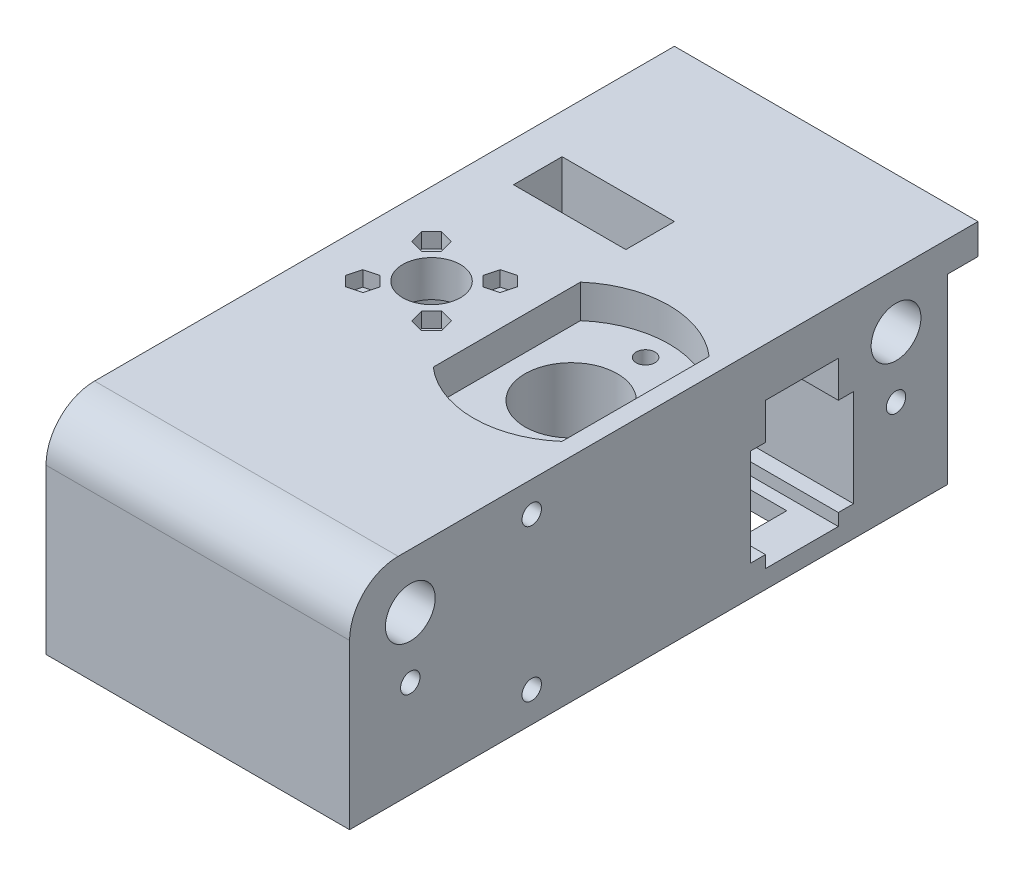
SolidWorks part; units mm, degrees
ref_plane "Front Plane" through (0, 0, 0) normal (0, 0, 1) x (1, 0, 0)
ref_plane "Top Plane" through (0, 0, 0) normal (0, 1, 0) x (1, 0, 0)
ref_plane "Right Plane" through (0, 0, 0) normal (1, 0, 0) x (0, 0, -1)
sketch "Sketch1" plane through (0, 0, 0) normal (1, 0, 0) x (0, 0, -1)
  line L0 (0, 0) -> (0, 30)
  line L1 (0, 30) -> (5, 30)
  line L2 (5, 30) -> (5, 35)
  line L3 (5, 35) -> (-98.5, 35)
  line L4 (-98.5, 35) -> (-98.5, 0)
  line L5 (-98.5, 0) -> (0, 0)
  dimension "D1" = 35
  dimension "D2" = 30
  dimension "D3" = 98.5
  dimension "D4" = 103.5
extrude "Boss-Extrude1" add sketch "Sketch1" along normal blind 50
sketch "Sketch2" plane through (0, 35, 0) normal (0, 1, 0) x (1, 0, 0)
  line L0 (50, 5) -> (50, -98.5) construction
  line L1 (50, 5) -> (0, 5) construction
  line L2 (36.5, -48.5) -> (13.5, -48.5) construction
  line L3 (36.5, -48.5) -> (36.5, -36.25) construction
  line L4 (36.5, -36.25) -> (36.5, -60.75) construction
  line L5 (13.5, -48.5) -> (13.5, -40.5) construction
  line L6 (13.5, -48.5) -> (19.1569, -42.8431) construction
  line L7 (13.5, -48.5) -> (7.8431, -42.8431) construction
  circle A0 centre (36.5, -48.5) radius 7.6
  circle A1 centre (13.5, -48.5) radius 4.75
  circle A2 centre (36.5, -36.25) radius 1.55
  circle A3 centre (36.5, -60.75) radius 1.55
  circle A4 centre (19.1569, -42.8431) radius 1.05
  circle A5 centre (19.1569, -54.1569) radius 1.05
  circle A6 centre (7.8431, -54.1569) radius 1.05
  circle A7 centre (7.8431, -42.8431) radius 1.05
  point P23 (13.5, -48.5)
  dimension "D1" = 15.2
  dimension "D2" = 13.5
  dimension "D3" = 53.5
  dimension "D5" = 9.5
  dimension "D8" = 3.1
  dimension "D9" = 3.1
  dimension "D13" = 2.1
  dimension "D16" = 11.3137
  dimension "D4" = 23
  dimension "D6" = 12.25
  dimension "D7" = 24.5
  dimension "D10" = 8
  dimension "D11" = 8
  dimension "D12" = 45
  dimension "D14" = 90
  dimension "D15" = 4
extrude "Cut-Extrude1" cut sketch "Sketch2" against normal through all
sketch "Sketch3" plane through (0, 35, 0) normal (0, 1, 0) x (1, 0, 0)
  line L0 (36.5, -32.4) -> (36.5, -64.6) construction
  line L1 (25.9, -36.3818) -> (25.9, -60.6182)
  line L2 (47.1, -36.3818) -> (47.1, -60.6182)
  arc A0 (25.9, -60.6182) -> (47.1, -60.6182) centre (36.5, -48.5) ccw
  arc A1 (47.1, -36.3818) -> (25.9, -36.3818) centre (36.5, -48.5) ccw
  dimension "D1" = 32.2
  dimension "D2" = 10.6
  dimension "D3" = 21.2
extrude "Cut-Extrude2" cut sketch "Sketch3" against normal blind 5.5
sketch "Sketch4" plane through (0, 0, 0) normal (0, -1, 0) x (1, 0, 0)
  circle A0 centre (13.5, 48.5) radius 11
  dimension "D1" = 22
extrude "Cut-Extrude3" cut sketch "Sketch4" against normal blind 29
sketch "Sketch5" plane through (0, 0, 0) normal (0, -1, 0) x (1, 0, 0)
  line L0 (36.5, 60.75) -> (41.5, 60.75) construction
  line L1 (36.5, 60.75) -> (38.1125, 63.5429) construction
  line L2 (36.5, 36.25) -> (41.5, 36.25) construction
  line L3 (39.725, 60.75) -> (38.1125, 63.5429)
  line L4 (38.1125, 63.5429) -> (34.8875, 63.5429)
  line L5 (34.8875, 63.5429) -> (33.275, 60.75)
  line L6 (33.275, 60.75) -> (34.8875, 57.9571)
  line L7 (34.8875, 57.9571) -> (38.1125, 57.9571)
  line L8 (38.1125, 57.9571) -> (39.725, 60.75)
  line L9 (38.1125, 39.0429) -> (34.8875, 39.0429)
  line L10 (34.8875, 39.0429) -> (33.275, 36.25)
  line L11 (33.275, 36.25) -> (34.8875, 33.4571)
  line L12 (34.8875, 33.4571) -> (38.1125, 33.4571)
  line L13 (38.1125, 33.4571) -> (39.725, 36.25)
  line L14 (39.725, 36.25) -> (38.1125, 39.0429)
  line L15 (38.1125, 39.0429) -> (36.5, 36.25) construction
  circle A0 centre (36.5, 60.75) radius 3.225 construction
  circle A1 centre (36.5, 36.25) radius 3.225 construction
  dimension "D3" = 6.45
  dimension "D4" = 6.45
  dimension "D1" = 5
  dimension "D2" = 5
  dimension "D5" = 60
  dimension "D6" = 60
extrude "Cut-Extrude4" cut sketch "Sketch5" against normal blind 5
sketch "Sketch6" plane through (0, 35, 0) normal (0, 1, 0) x (1, 0, 0)
  line L0 (19.1569, -42.8431) -> (24.1569, -42.8431) construction
  line L1 (19.1569, -42.8431) -> (21.3881, -42.2453) construction
  line L2 (21.3881, -42.2453) -> (19.7547, -40.6119)
  line L3 (19.7547, -40.6119) -> (17.5234, -41.2097)
  line L4 (17.5234, -41.2097) -> (16.9256, -43.441)
  line L5 (16.9256, -43.441) -> (18.559, -45.0744)
  line L6 (18.559, -45.0744) -> (20.7903, -44.4766)
  line L7 (20.7903, -44.4766) -> (21.3881, -42.2453)
  line L8 (19.1569, -42.8431) -> (13.5, -48.5) construction
  line L9 (21.3881, -54.7547) -> (20.7903, -52.5234)
  line L10 (20.7903, -52.5234) -> (18.559, -51.9256)
  line L11 (18.559, -51.9256) -> (16.9256, -53.559)
  line L12 (16.9256, -53.559) -> (17.5234, -55.7903)
  line L13 (17.5234, -55.7903) -> (19.7547, -56.3881)
  line L14 (19.7547, -56.3881) -> (21.3881, -54.7547)
  line L15 (7.2453, -56.3881) -> (9.4766, -55.7903)
  line L16 (9.4766, -55.7903) -> (10.0744, -53.559)
  line L17 (10.0744, -53.559) -> (8.441, -51.9256)
  line L18 (8.441, -51.9256) -> (6.2097, -52.5234)
  line L19 (6.2097, -52.5234) -> (5.6119, -54.7547)
  line L20 (5.6119, -54.7547) -> (7.2453, -56.3881)
  line L21 (5.6119, -42.2453) -> (6.2097, -44.4766)
  line L22 (6.2097, -44.4766) -> (8.441, -45.0744)
  line L23 (8.441, -45.0744) -> (10.0744, -43.441)
  line L24 (10.0744, -43.441) -> (9.4766, -41.2097)
  line L25 (9.4766, -41.2097) -> (7.2453, -40.6119)
  line L26 (7.2453, -40.6119) -> (5.6119, -42.2453)
  line L27 (7.8431, -42.8431) -> (13.5, -48.5) construction
  line L28 (7.8431, -42.8431) -> (9.4766, -41.2097) construction
  line L29 (7.8431, -42.8431) -> (10.0744, -43.441) construction
  circle A0 centre (19.1569, -42.8431) radius 2.31 construction
  circle A1 centre (19.1569, -54.1569) radius 2.31 construction
  circle A2 centre (7.8431, -54.1569) radius 2.31 construction
  circle A3 centre (7.8431, -42.8431) radius 2.31 construction
  point P38 (13.5, -48.5)
  dimension "D2" = 4.62
  dimension "D1" = 5
  dimension "D3" = 15
  dimension "D4" = 4
extrude "Cut-Extrude5" cut sketch "Sketch6" against normal blind 2.5
sketch "Sketch7" plane through (50, 0, 0) normal (1, 0, 0) x (0, 0, -1)
  line L0 (0, 0) -> (0, 30) construction
  line L1 (-30, 27) -> (-18, 27)
  line L2 (-30, 27) -> (-30, 3)
  line L3 (-30, 3) -> (-18, 3)
  line L4 (-18, 27) -> (-18, 3)
  line L5 (-98.5, 0) -> (0, 0) construction
  line L6 (5, 35) -> (-98.5, 35) construction
  line L7 (-8.5, 26) -> (-88.5, 26) construction
  line L8 (-88.5, 26) -> (-88.5, 16) construction
  line L9 (-8.5, 26) -> (-8.5, 16) construction
  line L10 (-88.5, 16) -> (-68.5, 30) construction
  line L11 (-68.5, 30) -> (-68.5, 5) construction
  circle A0 centre (-8.5, 26) radius 4.1
  circle A1 centre (-88.5, 26) radius 4.1
  circle A2 centre (-88.5, 16) radius 1.6
  circle A3 centre (-8.5, 16) radius 1.6
  circle A4 centre (-68.5, 30) radius 1.6
  circle A5 centre (-68.5, 5) radius 1.6
  dimension "D5" = 9
  dimension "D6" = 8.5
  dimension "D7" = 8.2
  dimension "D9" = 8.2
  dimension "D11" = 3.2
  dimension "D13" = 3.2
  dimension "D17" = 3.2
  dimension "D18" = 3.2
  dimension "D1" = 12
  dimension "D2" = 24
  dimension "D3" = 18
  dimension "D4" = 3
  dimension "D8" = 80
  dimension "D10" = 10
  dimension "D12" = 10
  dimension "D14" = 14
  dimension "D15" = 20
  dimension "D16" = 25
extrude "Cut-Extrude6" cut sketch "Sketch7" against normal through all
sketch "Sketch8" plane through (0, 0, 0) normal (-1, 0, 0) x (0, 0, 1)
  line L0 (8.5, 16) -> (13.8743, 16) construction
  line L1 (8.5, 16) -> (10.1125, 18.7929) construction
  line L2 (11.725, 16) -> (10.1125, 18.7929)
  line L3 (10.1125, 18.7929) -> (6.8875, 18.7929)
  line L4 (6.8875, 18.7929) -> (5.275, 16)
  line L5 (5.275, 16) -> (6.8875, 13.2071)
  line L6 (6.8875, 13.2071) -> (10.1125, 13.2071)
  line L7 (10.1125, 13.2071) -> (11.725, 16)
  line L8 (65.275, 30) -> (66.8875, 27.2071)
  line L9 (71.725, 30) -> (70.1125, 32.7929)
  line L10 (68.5, 30) -> (73.8743, 30) construction
  line L11 (70.1125, 27.2071) -> (71.725, 30)
  line L12 (70.1125, 32.7929) -> (66.8875, 32.7929)
  line L13 (68.5, 30) -> (70.1125, 32.7929) construction
  line L14 (66.8875, 27.2071) -> (70.1125, 27.2071)
  line L15 (66.8875, 32.7929) -> (65.275, 30)
  line L16 (65.275, 5) -> (66.8875, 2.2071)
  line L17 (71.725, 5) -> (70.1125, 7.7929)
  line L18 (68.5, 5) -> (73.8743, 5) construction
  line L19 (70.1125, 2.2071) -> (71.725, 5)
  line L20 (70.1125, 7.7929) -> (66.8875, 7.7929)
  line L21 (68.5, 5) -> (70.1125, 7.7929) construction
  line L22 (66.8875, 2.2071) -> (70.1125, 2.2071)
  line L23 (66.8875, 7.7929) -> (65.275, 5)
  line L24 (85.275, 16) -> (86.8875, 13.2071)
  line L25 (91.725, 16) -> (90.1125, 18.7929)
  line L26 (88.5, 16) -> (93.8743, 16) construction
  line L27 (90.1125, 13.2071) -> (91.725, 16)
  line L28 (90.1125, 18.7929) -> (86.8875, 18.7929)
  line L29 (88.5, 16) -> (90.1125, 18.7929) construction
  line L30 (86.8875, 13.2071) -> (90.1125, 13.2071)
  line L31 (86.8875, 18.7929) -> (85.275, 16)
  circle A0 centre (8.5, 16) radius 3.225 construction
  circle A1 centre (68.5, 30) radius 3.225 construction
  circle A2 centre (68.5, 5) radius 3.225 construction
  circle A3 centre (88.5, 16) radius 3.225 construction
  dimension "D1" = 6.45
  dimension "D2" = 60
  dimension "D3" = 80
  dimension "D4" = 14
  dimension "D5" = 25
  dimension "D6" = 60
  dimension "D7" = 60
extrude "Cut-Extrude7" cut sketch "Sketch8" against normal blind 35
sketch "Sketch9" plane through (50, 0, 0) normal (1, 0, 0) x (0, 0, -1)
  line L0 (-8.5, 26) -> (-8.5, 13) construction
  line L1 (-8.5, 13) -> (-24, 13) construction
  line L3 (-32.5, 5) -> (-15.5, 5)
  line L5 (-32.5, 21) -> (-15.5, 21)
  line L6 (-15.5, 5) -> (-15.5, 21)
  line L7 (-32.5, 5) -> (-15.5, 21) construction
  line L8 (-32.5, 21) -> (-15.5, 5) construction
  line L14 (-32.5, 5) -> (-32.5, 21)
  dimension "D1" = 13
  dimension "D2" = 15.5
  dimension "D3" = 17
  dimension "D4" = 16
extrude "Cut-Extrude8" cut sketch "Sketch9" against normal blind 48
sketch "Sketch10" plane through (0, 0, 0) normal (0, -1, 0) x (1, 0, 0)
  line L0 (43.5, 24) -> (6.5, 24) construction
  line L1 (6.5, 28) -> (43.5, 28)
  line L2 (6.5, 28) -> (6.5, 20)
  line L3 (6.5, 20) -> (43.5, 20)
  line L4 (43.5, 28) -> (43.5, 20)
  line L5 (50, -5) -> (0, -5) construction
  line L6 (0, 98.5) -> (0, 0) construction
  dimension "D1" = 37
  dimension "D2" = 8
  dimension "D3" = 29
  dimension "D4" = 6.5
extrude "Cut-Extrude9" cut sketch "Sketch10" against normal up to next and the other way through all
sketch "Sketch11" plane through (0, 27, 0) normal (0, -1, 0) x (1, 0, 0)
  line L0 (6.5, 20) -> (43.5, 20) construction
  line L1 (6.5, 28) -> (25, 28)
  line L2 (6.5, 28) -> (6.5, 20)
  line L3 (6.5, 20) -> (25, 20)
  line L4 (25, 28) -> (25, 20)
extrude "Cut-Extrude10" cut sketch "Sketch11" against normal up to next
fillet "Fillet1" radius 8 1 edges at (25, 35, 98.5)
